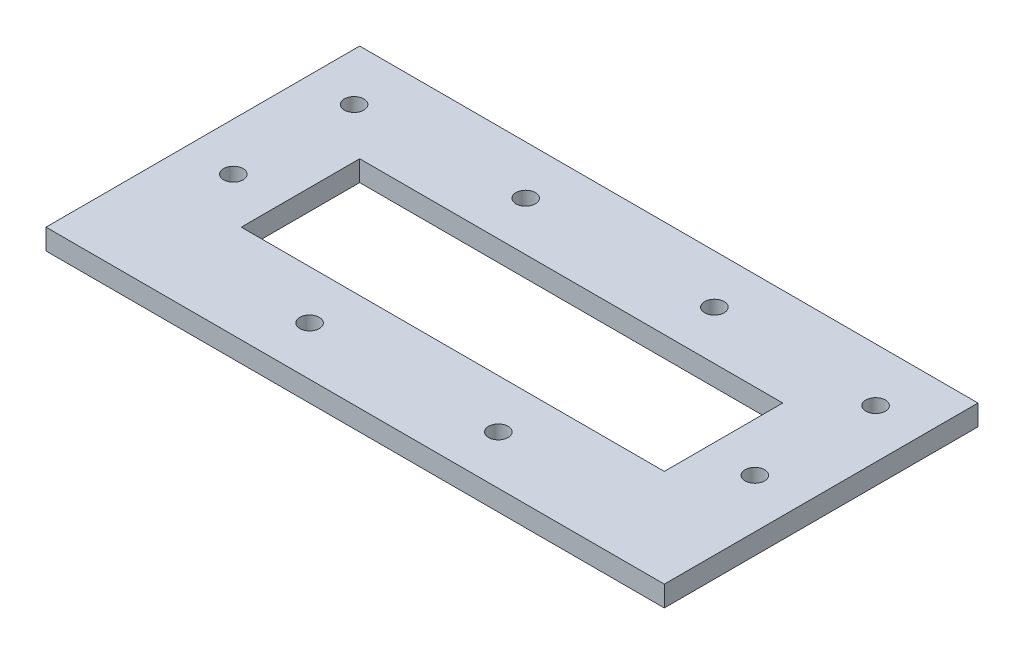
SolidWorks part; units mm, degrees
ref_plane "Front" through (0, 0, 0) normal (0, 0, 1) x (1, 0, 0)
ref_plane "Top" through (0, 0, 0) normal (0, 1, 0) x (1, 0, 0)
ref_plane "Right" through (0, 0, 0) normal (1, 0, 0) x (0, 0, -1)
sketch "Sketch2" plane through (0, 0, 0) normal (0, 1, 0) x (1, 0, 0)
  line L0 (-32.5, 24.0987) -> (-32.5, 9.0987) construction
  line L1 (-47.5, -24.0987) -> (47.5, -24.0987)
  line L2 (-47.5, -24.0987) -> (-47.5, 24.0987)
  line L3 (-47.5, 24.0987) -> (47.5, 24.0987)
  line L4 (47.5, -24.0987) -> (47.5, 24.0987)
  line L5 (-47.5, -24.0987) -> (47.5, 24.0987) construction
  line L6 (-47.5, 24.0987) -> (47.5, -24.0987) construction
  line L7 (-32.5, -9.0987) -> (32.5, -9.0987)
  line L8 (-32.5, -9.0987) -> (-32.5, 9.0987)
  line L9 (-32.5, 9.0987) -> (32.5, 9.0987)
  line L10 (32.5, -9.0987) -> (32.5, 9.0987)
  line L11 (-32.5, -9.0987) -> (32.5, 9.0987) construction
  line L12 (-32.5, 9.0987) -> (32.5, -9.0987) construction
  line L13 (32.5, 9.0987) -> (32.5, 24.0987) construction
  line L14 (-32.5, 16.5987) -> (32.5, 16.5987) construction
  line L15 (32.5, 9.0987) -> (47.5, 9.0987) construction
  line L16 (32.5, -9.0987) -> (47.5, -9.0987) construction
  line L17 (39.9789, 24.0987) -> (39.9789, -24.0987) construction
  line L18 (-47.5, 9.0987) -> (-32.5, 9.0987) construction
  line L19 (-47.5, -9.0987) -> (-32.5, -9.0987) construction
  line L20 (-32.5, -9.0987) -> (-32.5, -24.0987) construction
  line L21 (32.5, -9.0987) -> (32.5, -24.0987) construction
  line L22 (-40.149, 24.0987) -> (-40.149, -24.0987) construction
  line L23 (-32.5, -16.5987) -> (32.5, -16.5987) construction
  circle A0 centre (-14.5, 16.5987) radius 1.5
  circle A1 centre (14.5, 16.5987) radius 1.5
  circle A2 centre (-40.149, 15.8818) radius 1.5
  circle A3 centre (-40.149, -2.6627) radius 1.5
  circle A4 centre (39.9789, 15.8818) radius 1.5
  circle A5 centre (39.9789, -2.6627) radius 1.5
  circle A6 centre (-14.5, -16.5987) radius 1.5
  circle A7 centre (14.5, -16.5987) radius 1.5
  point P0 (0, 0)
  point P6 (0, 0)
  dimension "D7" = 18
  dimension "D8" = 18
  dimension "D1" = 48.1974
  dimension "D2" = 15
  dimension "D3" = 15
  dimension "D4" = 15
  dimension "D5" = 15
  dimension "D6" = 95
extrude "Boss-Extrude2" add sketch "Sketch2" along normal blind 3.175
